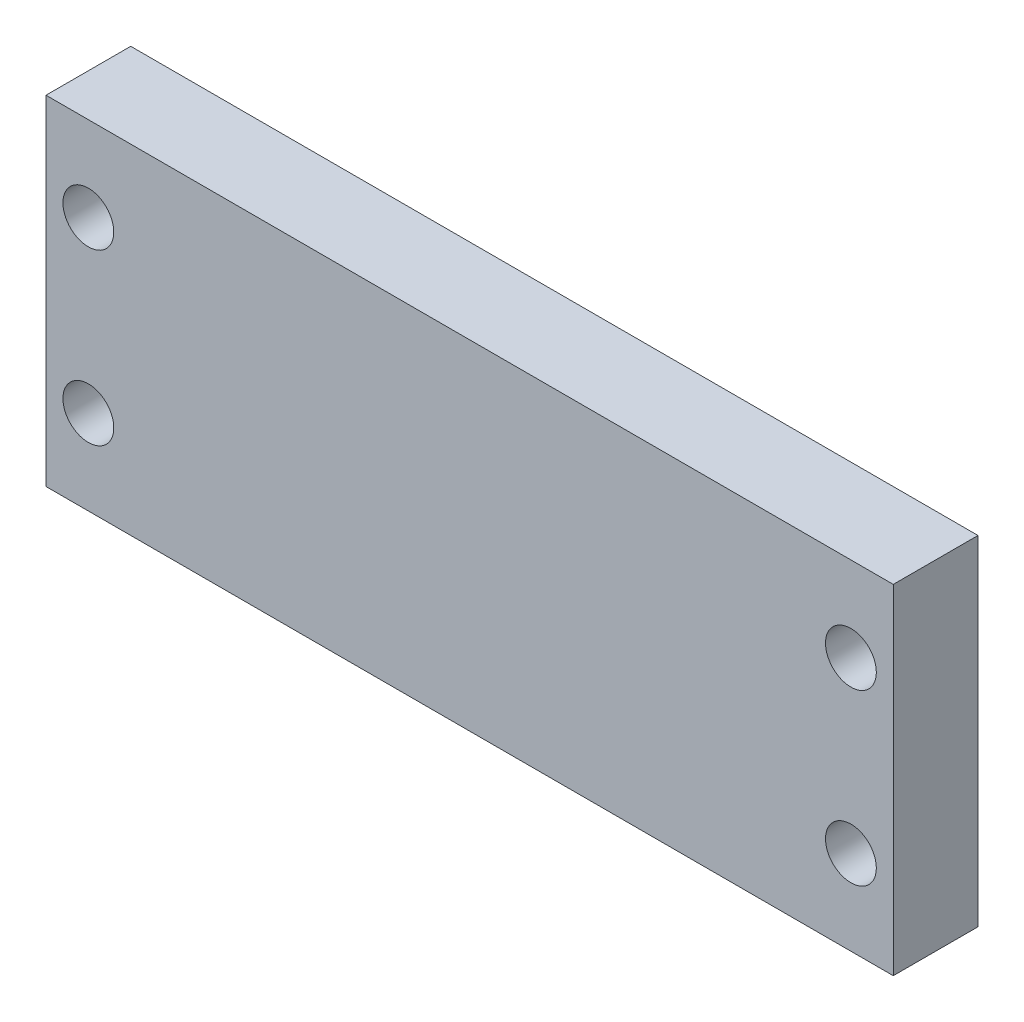
SolidWorks part; units mm, degrees
ref_plane "Front Plane" through (0, 0, 0) normal (0, 0, 1) x (1, 0, 0)
ref_plane "Top Plane" through (0, 0, 0) normal (0, 1, 0) x (1, 0, 0)
ref_plane "Right Plane" through (0, 0, 0) normal (1, 0, 0) x (0, 0, -1)
sketch "Sketch1" plane through (0, 0, 0) normal (0, 0, 1) x (1, 0, 0)
  line L1 (0, 0) -> (25, 0)
  line L2 (0, 0) -> (0, 20)
  line L3 (0, 20) -> (25, 20)
  line L4 (25, 0) -> (25, 20)
  circle A0 centre (22.5, 5) radius 1.5
  circle A1 centre (22.5, 15) radius 1.5
  dimension "D3" = 3
  dimension "D4" = 3
  dimension "D1" = 25
  dimension "D2" = 20
  dimension "D5" = 5
  dimension "D6" = 5
  dimension "D7" = 2.5
  dimension "D8" = 2.5
extrude "Boss-Extrude1" add sketch "Sketch1" along normal blind 5
mirror "Mirror1" about plane through (0, 0, 5) normal (1, 0, 0) of "Boss-Extrude1"
